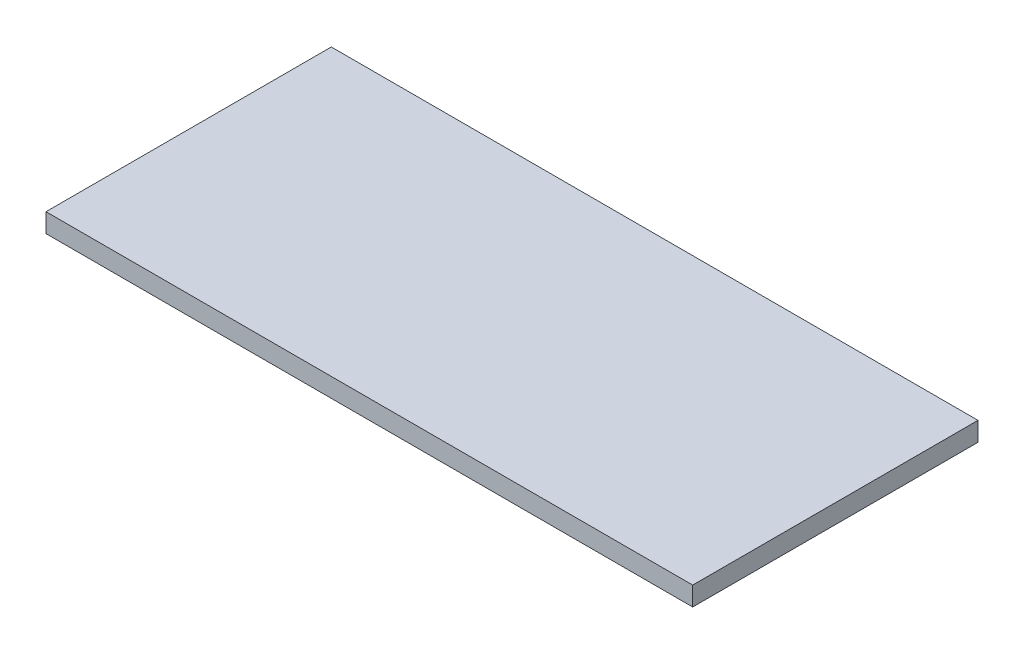
SolidWorks part; units mm, degrees
material "A-玻璃纤维"
ref_plane "前视基准面" through (0, 0, 0) normal (0, 0, 1) x (1, 0, 0)
ref_plane "上视基准面" through (0, 0, 0) normal (0, 1, 0) x (1, 0, 0)
ref_plane "右视基准面" through (0, 0, 0) normal (1, 0, 0) x (0, 0, -1)
other "Configuration Table"
sketch "草图1" plane through (0, 0, 0) normal (0, 1, 0) x (1, 0, 0)
  line L1 (0, 0) -> (68, 0)
  line L2 (0, 0) -> (0, 30)
  line L3 (0, 30) -> (68, 30)
  line L4 (68, 0) -> (68, 30)
  dimension "D1" = 68
  dimension "D2" = 30
extrude "凸台-拉伸1" add sketch "草图1" along normal blind 2
